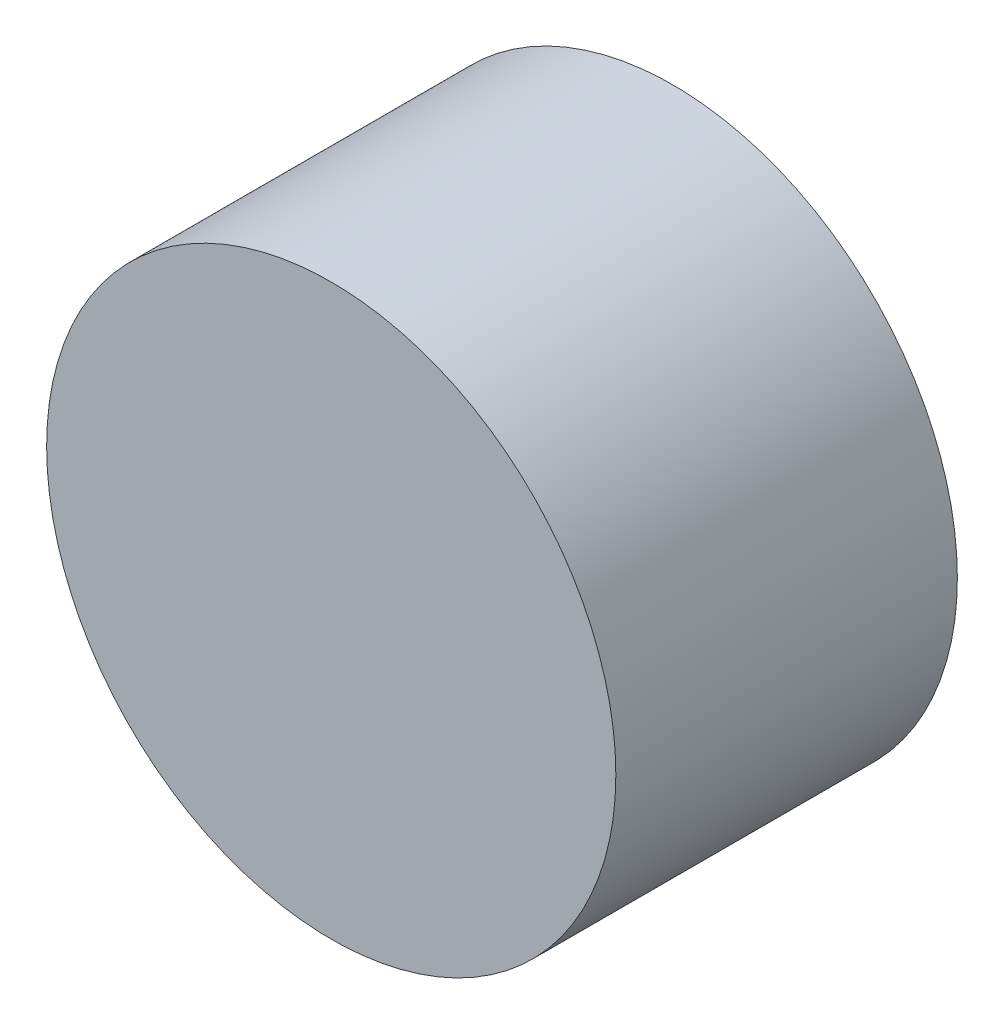
SolidWorks part; units mm, degrees
ref_plane "正面" through (0, 0, 0) normal (0, 0, 1) x (1, 0, 0)
ref_plane "平面" through (0, 0, 0) normal (0, 1, 0) x (1, 0, 0)
ref_plane "右側面" through (0, 0, 0) normal (1, 0, 0) x (0, 0, -1)
sketch "ｽｹｯﾁ1" plane through (0, 0, 0) normal (0, 0, 1) x (1, 0, 0)
  circle A0 centre (0, 0) radius 2.5
  dimension "D1" = 5
extrude "ﾎﾞｽ - 押し出し1" add sketch "ｽｹｯﾁ1" along normal blind 3
